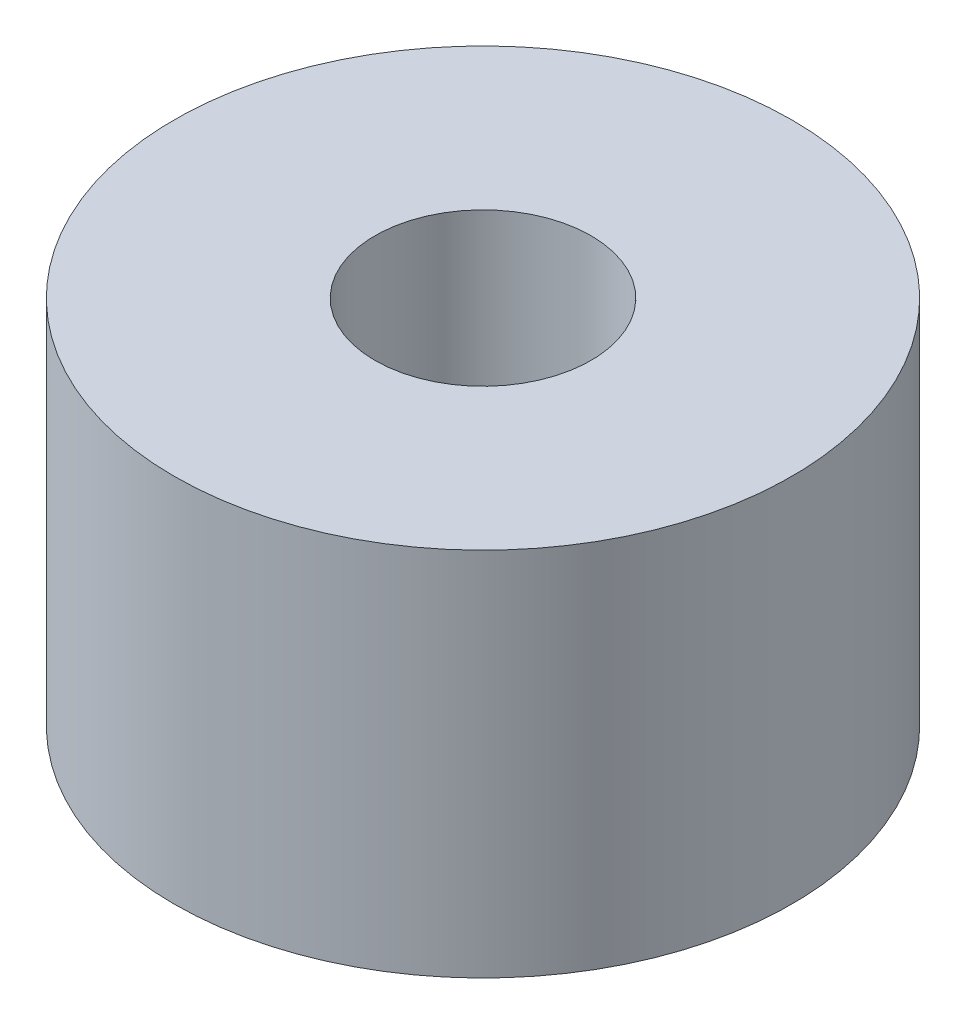
SolidWorks part; units mm, degrees
ref_plane "Alzado" through (0, 0, 0) normal (0, 0, 1) x (1, 0, 0)
ref_plane "Planta" through (0, 0, 0) normal (0, 1, 0) x (1, 0, 0)
ref_plane "Vista lateral" through (0, 0, 0) normal (1, 0, 0) x (0, 0, -1)
sketch "Croquis1" plane through (0, 0, 0) normal (0, 1, 0) x (1, 0, 0)
  circle A0 centre (0, 0) radius 10
  circle A1 centre (0, 0) radius 3.5
  dimension "D1" = 20
  dimension "D2" = 7
extrude "Extruir1" add sketch "Croquis1" along normal blind 12
